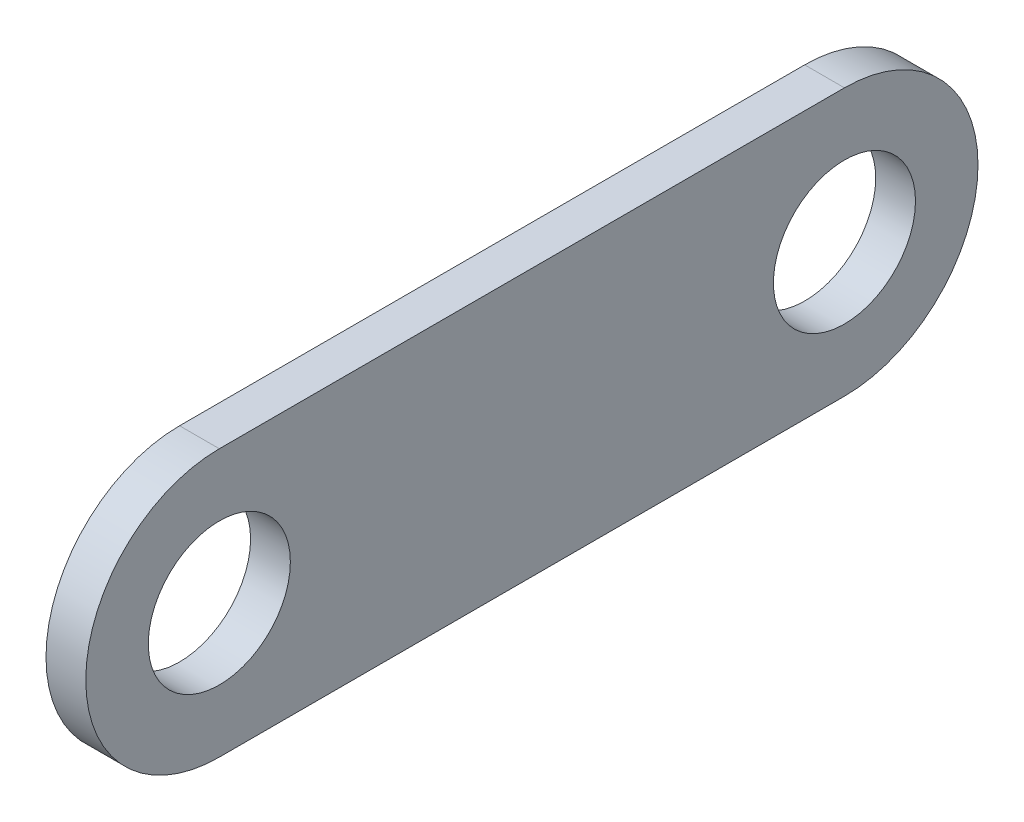
SolidWorks part; units mm, degrees
ref_plane "Front Plane" through (0, 0, 0) normal (0, 0, 1) x (1, 0, 0)
ref_plane "Top Plane" through (0, 0, 0) normal (0, 1, 0) x (1, 0, 0)
ref_plane "Right Plane" through (0, 0, 0) normal (1, 0, 0) x (0, 0, -1)
sketch "Sketch1" plane through (0, 0, 0) normal (1, 0, 0) x (0, 0, -1)
  line L0 (0, 0) -> (0, 12.9768) construction
  line L1 (-5.588, 2.3876) -> (5.588, 2.3876)
  line L2 (-5.588, -2.3876) -> (5.588, -2.3876)
  circle A0 centre (5.588, 0) radius 1.27
  circle A1 centre (-5.588, 0) radius 1.27
  arc A2 (-5.588, 2.3876) -> (-5.588, -2.3876) centre (-5.588, 0) ccw
  arc A3 (5.588, -2.3876) -> (5.588, 2.3876) centre (5.588, 0) ccw
  dimension "D1" = 5.588
  dimension "D2" = 5.588
extrude "Boss-Extrude1" add sketch "Sketch1" along normal blind 0.7112
